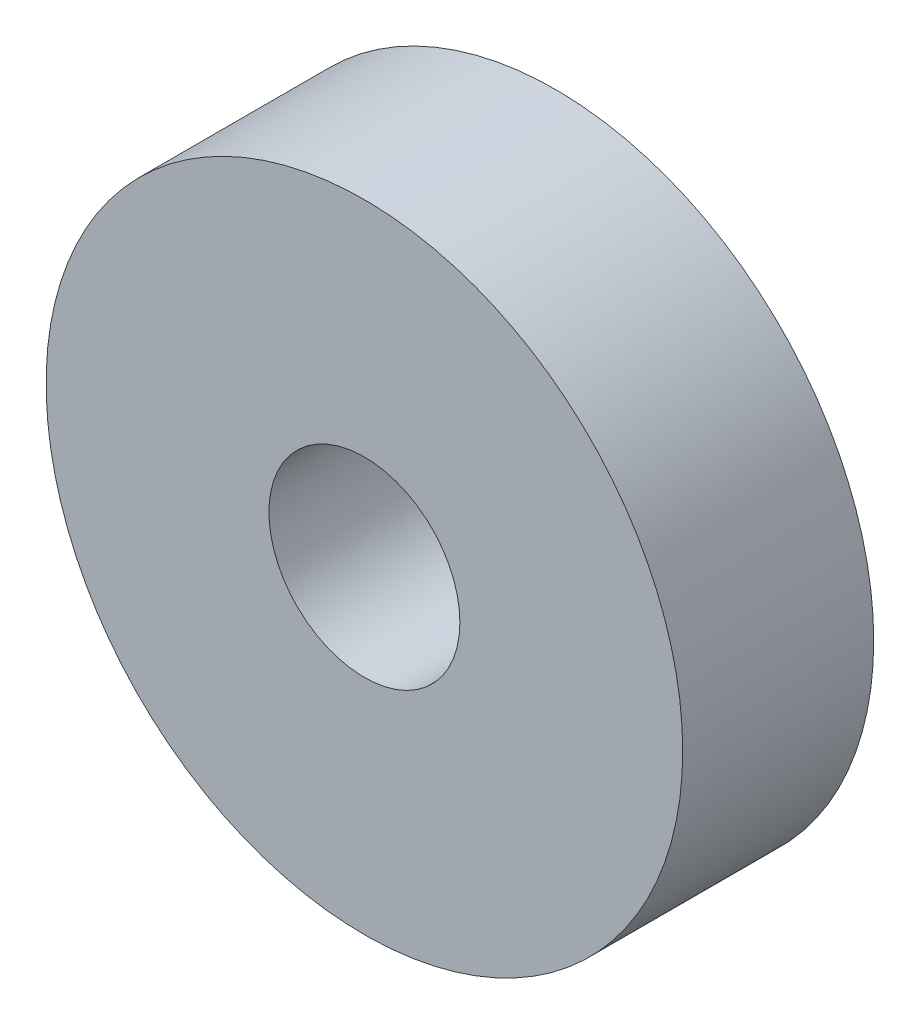
SolidWorks part; units mm, degrees
material "Acrílico (médio-alto impacto)"
ref_plane "Plano frontal" through (0, 0, 0) normal (0, 0, 1) x (1, 0, 0)
ref_plane "Plano superior" through (0, 0, 0) normal (0, 1, 0) x (1, 0, 0)
ref_plane "Plano direito" through (0, 0, 0) normal (1, 0, 0) x (0, 0, -1)
sketch "Esboço1" plane through (0, 0, 0) normal (0, 0, 1) x (1, 0, 0)
  circle A0 centre (0, 0) radius 5
  circle A1 centre (0, 0) radius 1.5
  dimension "D1" = 10
  dimension "D2" = 3
extrude "Ressalto-extrusão1" add sketch "Esboço1" along normal blind 3
